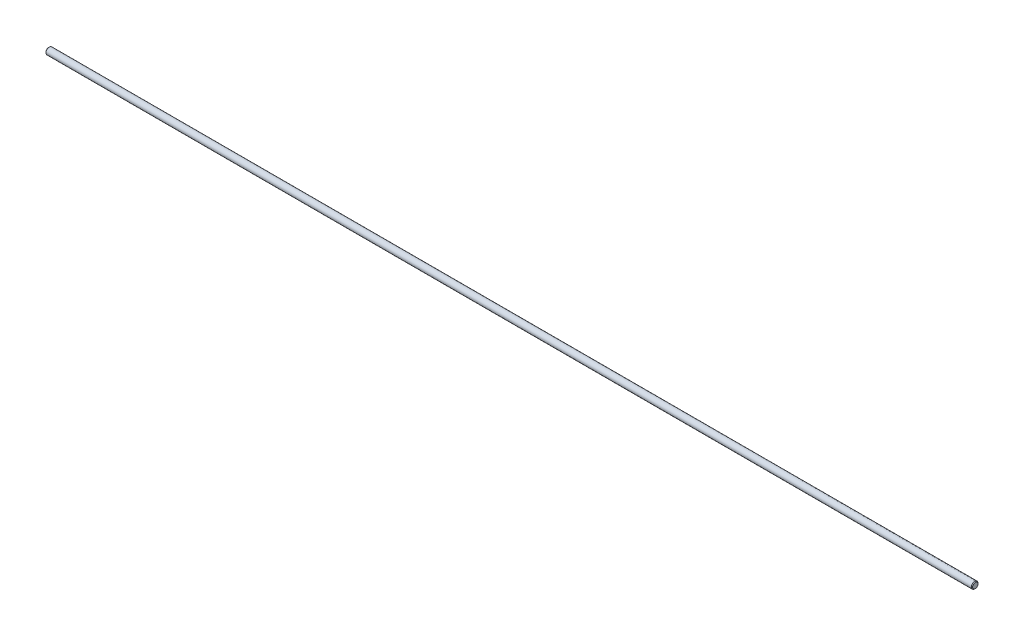
SolidWorks part; units mm, degrees
ref_plane "Front" through (0, 0, 0) normal (0, 0, 1) x (1, 0, 0)
ref_plane "Top" through (0, 0, 0) normal (0, 1, 0) x (1, 0, 0)
ref_plane "Right" through (0, 0, 0) normal (1, 0, 0) x (0, 0, -1)
sketch "Sketch1" plane through (0, 0, 0) normal (0, 0, 1) x (1, 0, 0)
  line L0 (-762, 0) -> (762, 0) construction
  line L1 (762, 4.7625) -> (762, -4.7625) construction
  line L2 (-762, 4.7625) -> (-762, -4.7625) construction
  dimension "Length" = 1524
  dimension "Diameter" = 9.525
sketch "Sketch2" plane through (0, 0, 0) normal (1, 0, 0) x (0, 0, -1)
  circle A0 centre (0, 0) radius 4.7625
extrude "Extrude1" add sketch "Sketch2" against normal up to vertex (762 mm away) and the other way up to vertex (762 mm away) up to point (-762, 4.7625, 0) other way up to point (762, 4.7625, 0)
chamfer "Chamfer1" distance 0.9525 angle 45 2 edges at (762, 0, -4.7625) (-762, 0, -4.7625)
sketch "Sketch3" plane through (-762, 0, 0) normal (-1, 0, 0) x (0, 0, 1)
  circle A0 centre (0, 0) radius 12.5408
extrude "Cut-Extrude1" cut sketch "Sketch3" against normal blind 203.2
chamfer "Chamfer2" distance 0.9525 angle 45 1 edges at (-558.8, 0, 4.7625)
equation "\"D1@Chamfer1\" = \"Diameter@Sketch1\"*.1"
